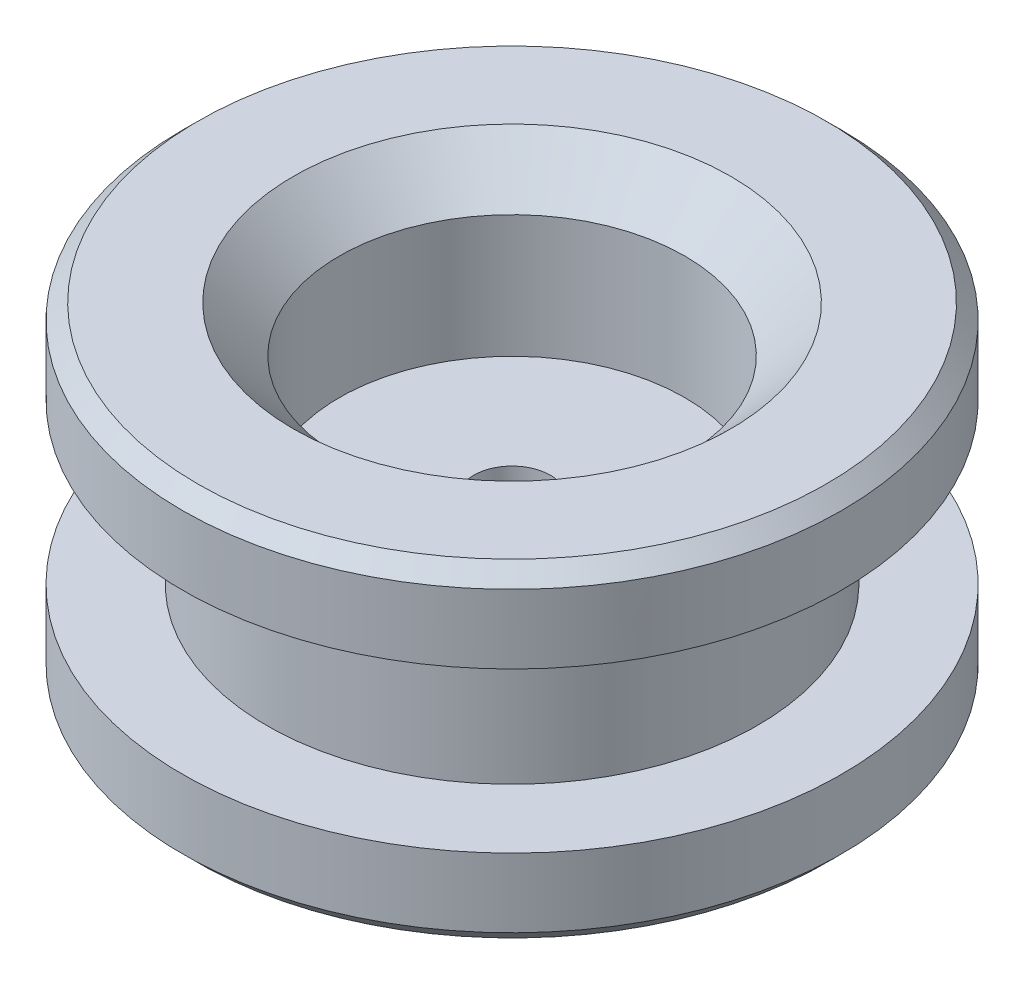
SolidWorks part; units mm, degrees
material "1060 Alloy"
ref_plane "Front Plane" through (0, 0, 0) normal (0, 0, 1) x (1, 0, 0)
ref_plane "Top Plane" through (0, 0, 0) normal (0, 1, 0) x (1, 0, 0)
ref_plane "Right Plane" through (0, 0, 0) normal (1, 0, 0) x (0, 0, -1)
sketch "Sketch1" plane through (0, 0, 0) normal (0, 0, 1) x (1, 0, 0)
  line L0 (0, 0) -> (0, 76.5215) construction
  line L1 (2.5, 40.5455) -> (11.2693, 40.5455)
  line L2 (11.2693, 40.5455) -> (11.2693, 51.5455)
  line L4 (11.2693, 51.5455) -> (21.5, 51.5455)
  line L5 (21.5, 51.5455) -> (21.5, 46.0455)
  line L6 (21.5, 46.0455) -> (16, 46.0455)
  line L7 (16, 46.0455) -> (16, 35.6455)
  line L8 (16, 35.6455) -> (21.5, 35.6455)
  line L9 (21.5, 35.6455) -> (21.5, 30.1455)
  line L10 (2.5, 30.1455) -> (21.5, 30.1455)
  line L11 (2.5, 40.5455) -> (2.5, 30.1455)
  dimension "D1" = 2.5
  dimension "D2" = 5.5
  dimension "D3" = 5.5
  dimension "D4" = 10.4
  dimension "D5" = 16
  dimension "D6" = 11.2693
  dimension "D7" = 11
revolve "Revolve1" add sketch "Sketch1" angle 360 about L0
chamfer "Chamfer1" distance 3 angle 45 1 edges at (0, 51.5455, -11.2693)
chamfer "Chamfer2" distance 1 angle 45 2 edges at (0, 30.1455, -21.5) (0, 51.5455, -21.5)
